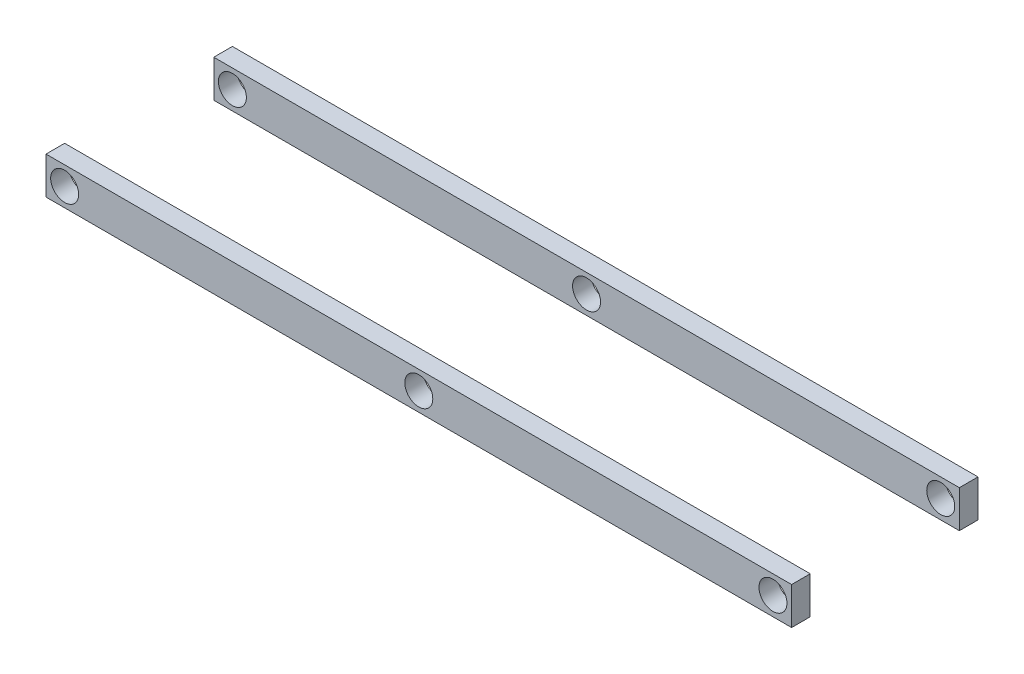
SolidWorks part; units mm, degrees
ref_plane "Front Plane" through (0, 0, 0) normal (0, 0, 1) x (1, 0, 0)
ref_plane "Top Plane" through (0, 0, 0) normal (0, 1, 0) x (1, 0, 0)
ref_plane "Right Plane" through (0, 0, 0) normal (1, 0, 0) x (0, 0, -1)
sketch "Sketch1" plane through (0, 0, 0) normal (0, 1, 0) x (1, 0, 0)
  line L1 (0, 0) -> (40, 0)
  line L2 (0, 0) -> (0, 10)
  line L3 (0, 10) -> (40, 10)
  line L4 (40, 0) -> (40, 10)
  dimension "D1" = 10
  dimension "D2" = 40
extrude "Boss-Extrude1" add sketch "Sketch1" along normal blind 2
sketch "Sketch4" plane through (0, 2, 0) normal (0, 1, 0) x (1, 0, 0)
  line L1 (0, 10) -> (0, 0) construction
  line L2 (0, 9) -> (0, 1)
  line L3 (0, 9) -> (40, 9)
  line L4 (40, 0) -> (40, 10) construction
  line L5 (40, 9) -> (40, 1)
  line L6 (40, 1) -> (0, 1)
  dimension "D2" = 8
extrude "Cut-Extrude2" cut sketch "Sketch4" against normal blind 2
sketch "Sketch5" plane through (0, 0, 0) normal (0, 0, 1) x (1, 0, 0)
  circle A0 centre (20, 1) radius 0.75
  circle A1 centre (1, 1) radius 0.75
  circle A2 centre (39, 1) radius 0.75
  dimension "D1" = 1.5
  dimension "D3" = 1.5
  dimension "D2" = 1.5
extrude "Cut-Extrude3" cut sketch "Sketch5" against normal through all
